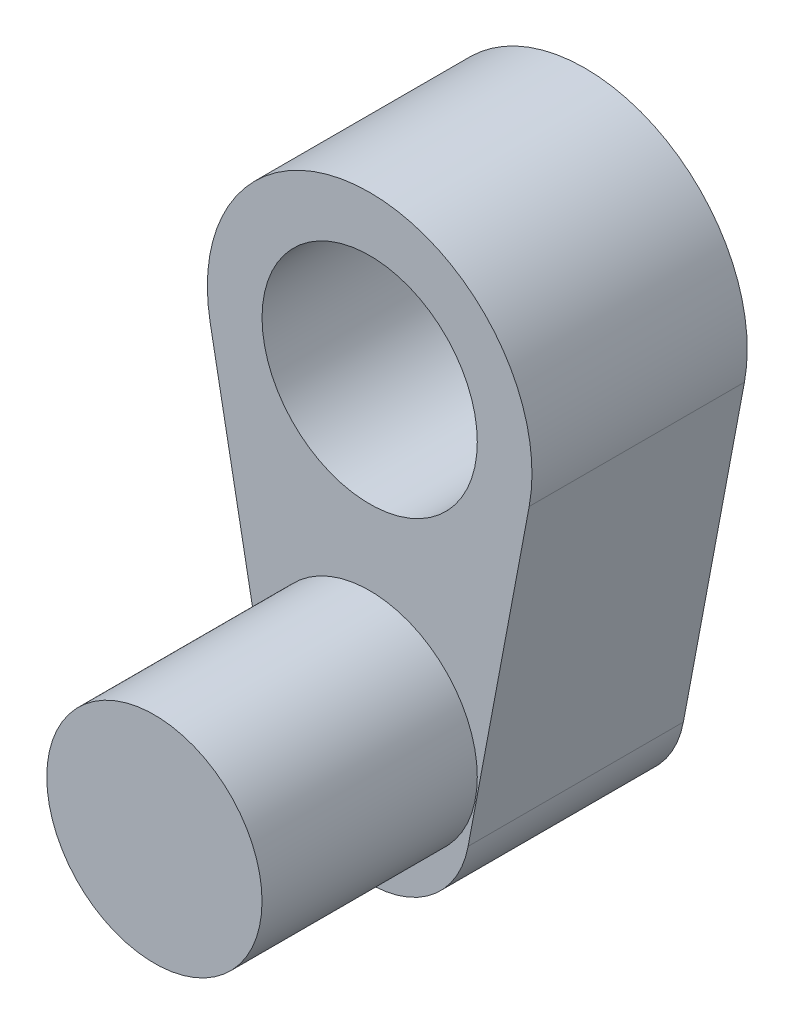
SolidWorks part; units mm, degrees
ref_plane "Front Plane" through (0, 0, 0) normal (0, 0, 1) x (1, 0, 0)
ref_plane "Top Plane" through (0, 0, 0) normal (0, 1, 0) x (1, 0, 0)
ref_plane "Right Plane" through (0, 0, 0) normal (1, 0, 0) x (0, 0, -1)
sketch "Sketch2" plane through (0, 0, 0) normal (0, 0, 1) x (1, 0, 0)
  line L1 (0, 7.9112) -> (0, -9.4931) construction
  line L3 (-3.7051, 4.386) -> (-2.2868, -3.1589)
  line L4 (3.7051, 4.386) -> (2.2868, -3.1589)
  arc A3 (-3.7051, 4.386) -> (3.7051, 4.386) centre (0, 5.0825) cw
  arc A4 (-2.2868, -3.1589) -> (2.2868, -3.1589) centre (0, -2.729) ccw
  circle A5 centre (0, 5.0825) radius 2.5
  point P10 (2.6588, -5.1391)
  point P11 (2.7932, -0.8595)
  point P12 (2.2868, -3.1589)
  dimension "D1" = 5
extrude "Boss-Extrude1" add sketch "Sketch2" along normal blind 5
sketch "Sketch5" plane through (0, 0, 5) normal (0, 0, 1) x (1, 0, 0)
  circle A0 centre (0, -1.6569) radius 2.5
  point P2 (0, -1.6569)
  dimension "D1" = 5
extrude "Boss-Extrude2" add sketch "Sketch5" along normal blind 5
scale "Scale1" scale about origin uniform scaling yes scale factor 0.6
